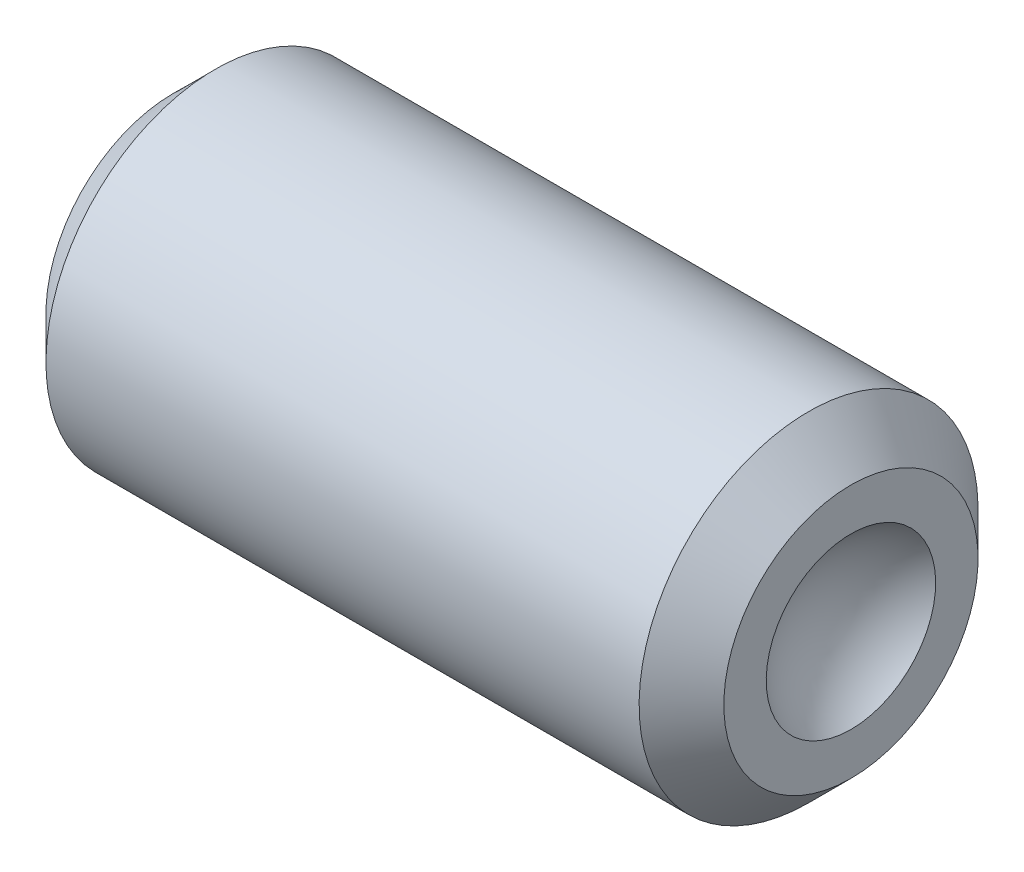
SolidWorks part; units mm, degrees
ref_plane "Front Plane" through (0, 0, 0) normal (0, 0, 1) x (1, 0, 0)
ref_plane "Top Plane" through (0, 0, 0) normal (0, 1, 0) x (1, 0, 0)
ref_plane "Right Plane" through (0, 0, 0) normal (1, 0, 0) x (0, 0, -1)
sketch "Sketch1" plane through (0, 0, 0) normal (0, 0, 1) x (1, 0, 0)
  line L0 (0, 0) -> (0, 1.5)
  line L1 (0, 1.5) -> (0.5, 2)
  line L2 (0.5, 2) -> (7.5, 2)
  line L3 (7.5, 2) -> (8, 1.5)
  line L4 (0, 0) -> (7.5, 0) construction
  line L5 (0.5, 2) -> (0.5, 1.5) construction
  line L6 (0.5, 1.5) -> (0.5, 1) construction
  line L7 (0.5, 1) -> (0.5, 0.5) construction
  line L8 (0.5, 0.5) -> (0.5, 0) construction
  line L9 (0.5, 1.5) -> (0, 1.5) construction
  line L10 (7.5, 2) -> (7.5, 0) construction
  line L11 (8, 1.5) -> (8, 1)
  line L12 (0, 0) -> (7.5, 0)
  arc A0 (7.5, 0) -> (8, 1) centre (8.75, 0) cw
  dimension "D1" = 45
  dimension "D2" = 4
  dimension "D3" = 8
  dimension "D4" = 2
revolve "Revolve1" add sketch "Sketch1" angle 360 about L12
sketch "Sketch2" plane through (0, 0, 0) normal (-1, 0, 0) x (0, 0, 1)
  line L1 (0, 1.1547) -> (-1, 0.5774)
  line L2 (-1, 0.5774) -> (-1, -0.5774)
  line L3 (-1, -0.5774) -> (0, -1.1547)
  line L4 (0, -1.1547) -> (1, -0.5774)
  line L5 (1, -0.5774) -> (1, 0.5774)
  line L6 (1, 0.5774) -> (0, 1.1547)
  circle A0 centre (0, 0) radius 1 construction
  dimension "D1" = 2
extrude "Cut-Extrude1" cut sketch "Sketch2" against normal offset from surface (6 mm away) 2 up to face at (8, -1.5, 0)
